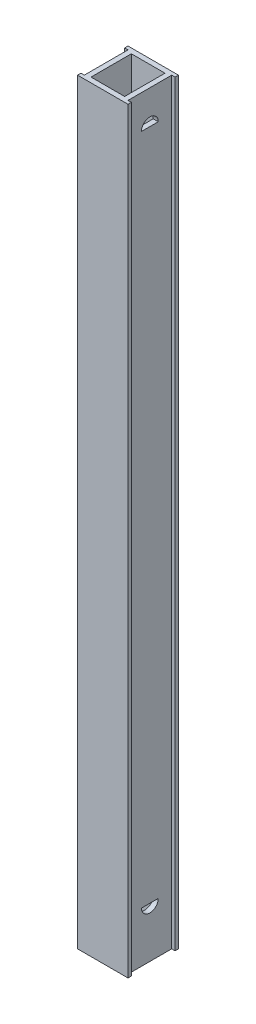
SolidWorks part; units mm, degrees
ref_plane "前视基准面" through (0, 0, 0) normal (0, 0, 1) x (1, 0, 0)
ref_plane "上视基准面" through (0, 0, 0) normal (0, 1, 0) x (1, 0, 0)
ref_plane "右视基准面" through (0, 0, 0) normal (1, 0, 0) x (0, 0, -1)
other "Configuration Table"
sketch "草图1" plane through (0, 0, 0) normal (0, 0, 1) x (1, 0, 0)
  line L0 (0, 0) -> (324.4923, 0) construction
  line L1 (0, 0) -> (0, 279.3401) construction
  line L2 (-15, 225) -> (15, 225)
  line L3 (-15, 225) -> (-15, -225)
  line L4 (-15, -225) -> (15, -225)
  line L5 (15, -225) -> (15, 225)
  point P6 (0, 225)
  point P10 (-15, 0)
  dimension "D1" = 450
  dimension "D2" = 30
extrude "凸台-拉伸1" add sketch "草图1" along normal blind 30
sketch "草图2" plane through (0, 225, 0) normal (0, 1, 0) x (1, 0, 0)
  line L0 (0, 0) -> (0, -20.1827) construction
  line L1 (0, -10) -> (15.4868, -10) construction
  line L2 (-15, -2) -> (-13, -2)
  line L3 (-13, -2) -> (-13, -28)
  line L4 (-13, -28) -> (-15, -28)
  line L5 (15, -30) -> (15, 0) construction
  line L6 (-15, -30) -> (-15, 0) construction
  line L7 (15, -28) -> (15, -2)
  line L8 (-15, -28) -> (-15, -2)
  line L9 (15, 0) -> (-15, 0) construction
  line L10 (15, -30) -> (-15, -30) construction
  line L11 (13, -28) -> (15, -28)
  line L12 (13, -2) -> (13, -28)
  line L13 (15, -2) -> (13, -2)
  dimension "D2" = 2
  dimension "D1" = 2
  dimension "D3" = 2
extrude "切除-拉伸1" cut sketch "草图2" against normal through all
shell "抽壳1" thickness 3
sketch "草图3" plane through (13, 0, 0) normal (1, 0, 0) x (0, 0, -1)
  line L0 (0, 0) -> (170.4874, 0) construction
  line L1 (-15, 225) -> (-15, -46.9872) construction
  line L2 (-20, 205) -> (-10, 205)
  line L3 (-2, 225) -> (-28, 225) construction
  line L4 (-20, -195) -> (-10, -195)
  line L5 (-2, -225) -> (-28, -225) construction
  arc A1 (-10, 205) -> (-20, 205) centre (-15, 205) ccw
  arc A2 (-10, -195) -> (-20, -195) centre (-15, -195) cw
  point P12 (0, 0)
  point P13 (-15, -195)
  point P14 (0, 0)
  point P15 (0, 0)
  point P18 (-15, -225)
  dimension "D1" = 20
  dimension "D2" = 5
  dimension "D3" = 30
  dimension "D4" = 5
extrude "切除-拉伸2" cut sketch "草图3" against normal through all
